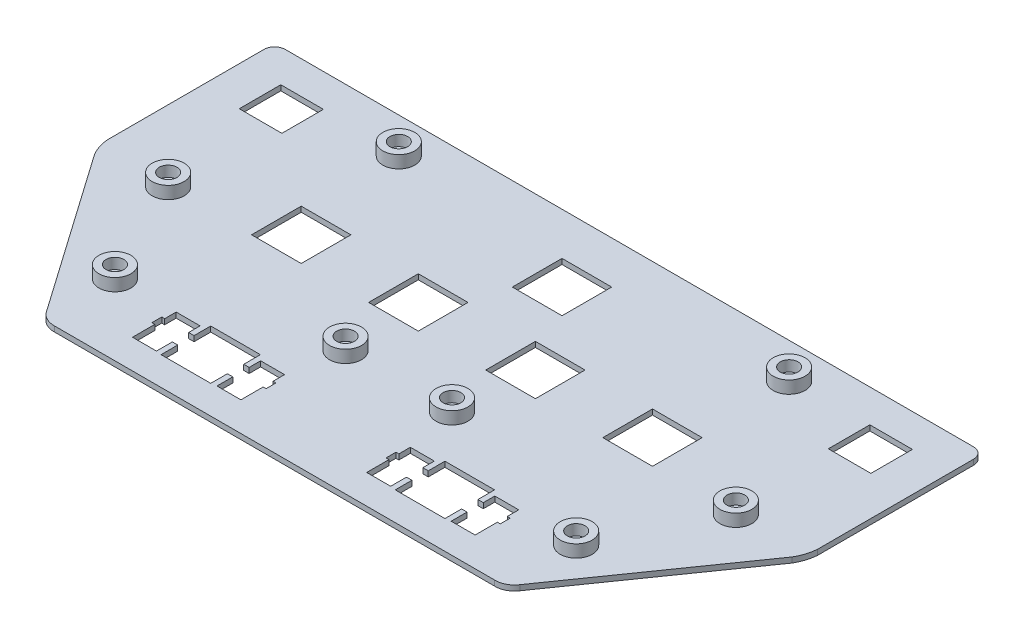
SolidWorks part; units mm, degrees
ref_plane "前视基准面" through (0, 0, 0) normal (0, 0, 1) x (1, 0, 0)
ref_plane "上视基准面" through (0, 0, 0) normal (0, 1, 0) x (1, 0, 0)
ref_plane "右视基准面" through (0, 0, 0) normal (1, 0, 0) x (0, 0, -1)
other "Configuration Table"
sketch "草图1" plane through (0, 0, 0) normal (0, 1, 0) x (1, 0, 0)
  line L0 (0, 0) -> (200, 0) construction
  line L1 (200, 0) -> (200, -100) construction
  line L2 (200, -100) -> (0, -100) construction
  line L3 (0, -100) -> (0, 0) construction
  line L4 (0, -100) -> (35, -100) construction
  line L5 (200, -100) -> (165, -100) construction
  line L6 (0, -50) -> (35, -100) construction
  line L7 (165, -100) -> (200, -50) construction
  line L8 (200, -50) -> (200, -47) construction
  line L9 (0, -50) -> (0, -47) construction
  line L10 (35, -100) -> (38, -100) construction
  line L11 (165, -100) -> (162, -100) construction
  line L12 (0, 0) -> (0, -3) construction
  line L13 (0, -3) -> (3, -3) construction
  line L14 (200, 0) -> (200, -3) construction
  line L15 (200, -3) -> (197, -3) construction
  line L16 (197, 0) -> (3, 0)
  line L17 (0, -3) -> (0, -47)
  line L18 (1.7204, -52.4577) -> (33.2796, -97.5423)
  line L19 (38, -100) -> (162, -100)
  line L20 (166.7204, -97.5423) -> (198.2796, -52.4577)
  line L21 (200, -47) -> (200, -3)
  line L22 (0, 0) -> (0, -5) construction
  line L23 (0, -5) -> (5, -5) construction
  line L24 (200, 0) -> (200, -5) construction
  line L25 (200, -5) -> (195, -5) construction
  line L26 (100, 0) -> (100, -12) construction
  line L35 (107, -12) -> (93, -12) construction
  line L36 (93, -26) -> (90.5, -26) construction
  line L37 (93, -12) -> (107, -12)
  line L38 (93, -12) -> (93, -26)
  line L39 (93, -26) -> (107, -26)
  line L40 (107, -12) -> (107, -26)
  line L41 (90.5, -26) -> (90.5, -36) construction
  line L42 (107, -26) -> (109.5, -26) construction
  line L43 (109.5, -26) -> (109.5, -36) construction
  line L44 (76.5, -36) -> (57.5, -36) construction
  line L45 (90.5, -36) -> (76.5, -36)
  line L46 (90.5, -36) -> (90.5, -50)
  line L47 (90.5, -50) -> (76.5, -50)
  line L48 (76.5, -36) -> (76.5, -50)
  line L49 (109.5, -36) -> (123.5, -36)
  line L50 (109.5, -36) -> (109.5, -50)
  line L51 (109.5, -50) -> (123.5, -50)
  line L52 (123.5, -36) -> (123.5, -50)
  line L53 (123.5, -36) -> (142.5, -36) construction
  line L54 (57.5, -36) -> (43.5, -36)
  line L55 (57.5, -36) -> (57.5, -50)
  line L56 (57.5, -50) -> (43.5, -50)
  line L57 (43.5, -36) -> (43.5, -50)
  line L58 (67, -36) -> (67, -78) construction
  line L59 (142.5, -36) -> (156.5, -36)
  line L60 (142.5, -36) -> (142.5, -50)
  line L61 (142.5, -50) -> (156.5, -50)
  line L62 (156.5, -36) -> (156.5, -50)
  line L63 (133, -36) -> (133, -78) construction
  line L64 (60, -78) -> (74, -78) construction
  line L65 (140, -78) -> (126, -78) construction
  line L66 (5, -5) -> (5, -15.1) construction
  line L67 (60, -78) -> (74, -78)
  line L69 (60, -92) -> (74, -92)
  line L71 (140, -78) -> (126, -78)
  line L73 (140, -92) -> (126, -92)
  line L75 (5, -15.1) -> (11, -15.1) construction
  line L76 (195, -5) -> (195, -15.1) construction
  line L77 (11, -20.95) -> (23, -20.95)
  line L78 (11, -20.95) -> (11, -9.25)
  line L79 (11, -9.25) -> (23, -9.25)
  line L80 (23, -20.95) -> (23, -9.25)
  line L81 (195, -15.1) -> (189, -15.1) construction
  line L82 (74, -78) -> (74, -82.7)
  line L83 (189, -20.95) -> (177, -20.95)
  line L84 (189, -20.95) -> (189, -9.25)
  line L85 (189, -9.25) -> (177, -9.25)
  line L86 (177, -20.95) -> (177, -9.25)
  line L87 (74, -92) -> (74, -87.3)
  line L88 (74, -82.7) -> (75.525, -82.7)
  line L89 (74, -87.3) -> (75.525, -87.3)
  line L90 (75.525, -82.7) -> (75.525, -79.47)
  line L91 (75.525, -87.3) -> (75.525, -91.77)
  line L92 (75.525, -79.47) -> (82.275, -79.47)
  line L93 (82.275, -79.47) -> (82.275, -82.7)
  line L94 (82.275, -82.7) -> (83.1, -82.7)
  line L95 (83.1, -82.7) -> (83.1, -85.5)
  line L96 (83.1, -85.5) -> (82.275, -85.5)
  line L97 (82.275, -85.5) -> (82.275, -91.77)
  line L98 (82.275, -91.77) -> (75.525, -91.77)
  line L101 (60, -78) -> (60, -82.7)
  line L102 (60, -92) -> (60, -87.3)
  line L103 (60, -82.7) -> (58.475, -82.7)
  line L104 (58.475, -82.7) -> (58.475, -79.47)
  line L105 (58.475, -79.47) -> (51.725, -79.47)
  line L106 (51.725, -79.47) -> (51.725, -82.7)
  line L107 (51.725, -82.7) -> (50.9, -82.7)
  line L108 (50.9, -82.7) -> (50.9, -85.5)
  line L109 (50.9, -85.5) -> (51.725, -85.5)
  line L110 (51.725, -85.5) -> (51.725, -91.77)
  line L111 (51.725, -91.77) -> (58.475, -91.77)
  line L112 (58.475, -91.77) -> (58.475, -87.3)
  line L113 (58.475, -87.3) -> (60, -87.3)
  line L114 (140, -78) -> (140, -82.7)
  line L115 (140, -82.7) -> (141.525, -82.7)
  line L116 (141.525, -82.7) -> (141.525, -79.47)
  line L117 (141.525, -79.47) -> (148.275, -79.47)
  line L118 (148.275, -79.47) -> (148.275, -82.7)
  line L119 (148.275, -82.7) -> (149.1, -82.7)
  line L120 (149.1, -82.7) -> (149.1, -85.5)
  line L121 (149.1, -85.5) -> (148.275, -85.5)
  line L122 (148.275, -85.5) -> (148.275, -91.77)
  line L123 (148.275, -91.77) -> (141.525, -91.77)
  line L124 (141.525, -91.77) -> (141.525, -87.3)
  line L125 (141.525, -87.3) -> (140, -87.3)
  line L126 (140, -87.3) -> (140, -92)
  line L127 (126, -78) -> (126, -82.7)
  line L128 (126, -82.7) -> (124.475, -82.7)
  line L129 (124.475, -82.7) -> (124.475, -79.47)
  line L130 (124.475, -79.47) -> (117.725, -79.47)
  line L131 (117.725, -79.47) -> (117.725, -82.7)
  line L132 (117.725, -82.7) -> (116.9, -82.7)
  line L133 (116.9, -82.7) -> (116.9, -85.5)
  line L134 (116.9, -85.5) -> (117.725, -85.5)
  line L135 (117.725, -85.5) -> (117.725, -91.77)
  line L136 (117.725, -91.77) -> (124.475, -91.77)
  line L137 (124.475, -91.77) -> (124.475, -87.3)
  line L138 (124.475, -87.3) -> (126, -87.3)
  line L139 (126, -87.3) -> (126, -92)
  arc A0 (200, -47) -> (198.2796, -52.4577) centre (200, -50) ccw construction
  arc A1 (200, -47) -> (198.2796, -52.4577) centre (197.1388, -49.0981) ccw construction
  arc A2 (200, -47) -> (198.2796, -52.4577) centre (193.7549, -48.0314) ccw construction
  arc A3 (200, -47) -> (198.2796, -52.4577) centre (187.718, -46.1284) cw
  arc A4 (0, -47) -> (1.7204, -52.4577) centre (0, -50) cw construction
  arc A5 (0, -47) -> (1.7204, -52.4577) centre (2.8612, -49.0981) cw construction
  arc A6 (0, -47) -> (1.7204, -52.4577) centre (6.2451, -48.0314) cw construction
  arc A7 (0, -47) -> (1.7204, -52.4577) centre (12.282, -46.1284) ccw
  arc A8 (38, -100) -> (33.2796, -97.5423) centre (35, -100) ccw construction
  arc A9 (38, -100) -> (33.2796, -97.5423) centre (36.3854, -97.3391) ccw construction
  arc A10 (33.2796, -97.5423) -> (38, -100) centre (37.8228, -94.5784) ccw
  arc A11 (162, -100) -> (166.7204, -97.5423) centre (165, -100) cw construction
  arc A12 (162, -100) -> (166.7204, -97.5423) centre (163.6146, -97.3391) cw construction
  arc A13 (162, -100) -> (166.7204, -97.5423) centre (162.1772, -94.5784) ccw
  arc A14 (0, -3) -> (3, 0) centre (3, -3) cw
  arc A15 (200, -3) -> (197, 0) centre (197, -3) ccw
  point P48 (100, -12)
  point P75 (67, -78)
  point P78 (133, -78)
  dimension "D12" = 3
  dimension "D10" = 3
  dimension "D1" = 200
  dimension "D2" = 100
  dimension "D3" = 35
  dimension "D4" = 35
  dimension "D5" = 3
  dimension "D6" = 3
  dimension "D7" = 3
  dimension "D8" = 3
  dimension "D9" = 44
  dimension "D11" = 44
  dimension "D13" = 5
  dimension "D14" = 5
  dimension "D15" = 5
  dimension "D16" = 5
  dimension "D17" = 10.1
  dimension "D18" = 6
  dimension "D19" = 10.1
  dimension "D20" = 6
  dimension "D21" = 12
  dimension "D22" = 14
  dimension "D23" = 14
  dimension "D24" = 2.5
  dimension "D25" = 10
  dimension "D26" = 2.5
  dimension "D27" = 10
  dimension "D28" = 14
  dimension "D29" = 14
  dimension "D30" = 14
  dimension "D31" = 14
  dimension "D32" = 19
  dimension "D33" = 14
  dimension "D34" = 14
  dimension "D35" = 19
  dimension "D36" = 14
  dimension "D37" = 14
  dimension "D38" = 42
  dimension "D39" = 42
  dimension "D40" = 14
  dimension "D41" = 14
  dimension "D42" = 4.7
  dimension "D43" = 14
  dimension "D44" = 12
  dimension "D45" = 11.7
  dimension "D46" = 4.7
  dimension "D47" = 4.7
  dimension "D48" = 11.7
  dimension "D49" = 12
  dimension "D50" = 4.7
  dimension "D51" = 4.6
  dimension "D52" = 4.6
  dimension "D53" = 1.525
  dimension "D54" = 1.525
  dimension "D55" = 1.525
  dimension "D56" = 3.23
  dimension "D57" = 3.23
  dimension "D58" = 6.75
  dimension "D59" = 6.75
  dimension "D60" = 3.23
  dimension "D61" = 0.825
  dimension "D62" = 2.8
  dimension "D63" = 0.825
  dimension "D64" = 6.27
  dimension "D65" = 3.23
  dimension "D66" = 0.825
  dimension "D67" = 2.8
  dimension "D68" = 0.825
  dimension "D69" = 6.27
  dimension "D70" = 6.75
  dimension "D71" = 4.7
  dimension "D72" = 1.525
  dimension "D73" = 3.23
  dimension "D74" = 6.75
  dimension "D75" = 3.23
  dimension "D76" = 0.825
  dimension "D77" = 2.8
  dimension "D78" = 0.825
  dimension "D79" = 6.27
  dimension "D80" = 6.75
  dimension "D81" = 4.47
  dimension "D82" = 1.525
  dimension "D83" = 4.7
  dimension "D84" = 4.7
  dimension "D85" = 1.525
  dimension "D86" = 3.23
  dimension "D87" = 6.75
  dimension "D88" = 3.23
  dimension "D89" = 0.825
  dimension "D90" = 2.8
  dimension "D91" = 0.825
  dimension "D92" = 6.27
  dimension "D93" = 6.75
  dimension "D94" = 4.47
  dimension "D95" = 1.525
  dimension "D96" = 4.7
extrude "凸台-拉伸1" add sketch "草图1" along normal blind 1.5
sketch "草图2" plane through (0, 0, 0) normal (0, 1, 0) x (1, 0, 0)
  line L6 (0, 0) -> (0, -100) construction
  line L7 (0, 0) -> (200, 0) construction
  line L8 (0, -100) -> (200, -100) construction
  line L9 (200, -100) -> (200, 0) construction
  line L10 (0, -100) -> (35, -100) construction
  line L11 (200, -100) -> (165, -100) construction
  line L12 (200, -47) -> (200, -3)
  line L13 (197, 0) -> (3, 0)
  line L14 (0, -3) -> (0, -47)
  line L15 (1.7204, -52.4577) -> (33.2796, -97.5423)
  line L16 (38, -100) -> (162, -100)
  line L17 (166.7204, -97.5423) -> (198.2796, -52.4577)
  line L18 (200, -47) -> (200, -3) construction
  line L19 (197, 0) -> (3, 0) construction
  line L20 (0, -3) -> (0, -47) construction
  line L22 (38, -100) -> (162, -100) construction
  line L24 (35, -100) -> (0, -50) construction
  line L25 (165, -100) -> (200, -50) construction
  line L26 (0, -50) -> (20, -50) construction
  line L27 (45, 0) -> (45, -10) construction
  line L28 (200, 0) -> (155, 0) construction
  line L29 (155, 0) -> (155, -10) construction
  line L30 (200, -50) -> (180, -50) construction
  line L31 (165, -100) -> (165, -80) construction
  line L32 (35, -100) -> (35, -80) construction
  line L33 (35, -80) -> (35, -65) construction
  line L34 (35, -65) -> (85, -65) construction
  line L35 (165, -80) -> (165, -65) construction
  line L36 (165, -65) -> (115, -65) construction
  circle A6 centre (45, -10) radius 2.5
  circle A7 centre (155, -10) radius 2.5
  circle A8 centre (20, -50) radius 2.5
  circle A9 centre (35, -80) radius 2.5
  circle A10 centre (85, -65) radius 2.5
  circle A11 centre (180, -50) radius 2.5
  arc A12 (198.2796, -52.4577) -> (200, -47) centre (187.718, -46.1284) ccw
  arc A13 (200, -3) -> (197, 0) centre (197, -3) ccw
  arc A14 (3, 0) -> (0, -3) centre (3, -3) ccw
  arc A15 (0, -47) -> (1.7204, -52.4577) centre (12.282, -46.1284) ccw
  arc A16 (33.2796, -97.5423) -> (38, -100) centre (37.8228, -94.5784) ccw
  arc A17 (162, -100) -> (166.7204, -97.5423) centre (162.1772, -94.5784) ccw
  arc A18 (198.2796, -52.4577) -> (200, -47) centre (187.718, -46.1284) ccw construction
  arc A19 (200, -3) -> (197, 0) centre (197, -3) ccw construction
  arc A20 (3, 0) -> (0, -3) centre (3, -3) ccw construction
  arc A21 (0, -47) -> (1.7204, -52.4577) centre (12.282, -46.1284) ccw construction
  arc A22 (33.2796, -97.5423) -> (38, -100) centre (37.8228, -94.5784) ccw construction
  arc A23 (162, -100) -> (166.7204, -97.5423) centre (162.1772, -94.5784) ccw construction
  circle A24 centre (165, -80) radius 2.5
  circle A25 centre (115, -65) radius 2.5
  circle A26 centre (35, -80) radius 4.5
  circle A27 centre (20, -50) radius 4.5
  circle A28 centre (45, -10) radius 4.5
  circle A29 centre (85, -65) radius 4.5
  circle A30 centre (115, -65) radius 4.5
  circle A31 centre (165, -80) radius 4.5
  circle A32 centre (155, -10) radius 4.5
  circle A33 centre (180, -50) radius 4.5
  point P63 (0, 0)
  dimension "D16" = 5
  dimension "D17" = 5
  dimension "D18" = 5
  dimension "D19" = 5
  dimension "D20" = 5
  dimension "D21" = 5
  dimension "D22" = 5
  dimension "D23" = 5
  dimension "D2" = 35
  dimension "D3" = 200
  dimension "D4" = 35
  dimension "D5" = 45
  dimension "D6" = 10
  dimension "D7" = 45
  dimension "D8" = 10
  dimension "D9" = 20
  dimension "D10" = 20
  dimension "D11" = 20
  dimension "D12" = 20
  dimension "D13" = 15
  dimension "D14" = 50
  dimension "D15" = 50
  dimension "D1" = 0
  dimension "D24" = 2
extrude "凸台-拉伸2" add sketch "草图2" along normal blind 5
sketch "草图3" plane through (0, 0, 0) normal (0, 1, 0) x (1, 0, 0)
  circle A8 centre (180, -50) radius 2.5 construction
  circle A9 centre (165, -80) radius 2.5 construction
  circle A10 centre (115, -65) radius 2.5 construction
  circle A11 centre (155, -10) radius 2.5 construction
  circle A12 centre (45, -10) radius 2.5 construction
  circle A13 centre (20, -50) radius 2.5 construction
  circle A14 centre (35, -80) radius 2.5 construction
  circle A15 centre (85, -65) radius 2.5 construction
  circle A16 centre (180, -50) radius 2.5
  circle A17 centre (165, -80) radius 2.5
  circle A18 centre (115, -65) radius 2.5
  circle A19 centre (155, -10) radius 2.5
  circle A20 centre (45, -10) radius 2.5
  circle A21 centre (20, -50) radius 2.5
  circle A22 centre (35, -80) radius 2.5
  circle A23 centre (85, -65) radius 2.5
extrude "凸台-拉伸3" add sketch "草图3" along normal blind 2
